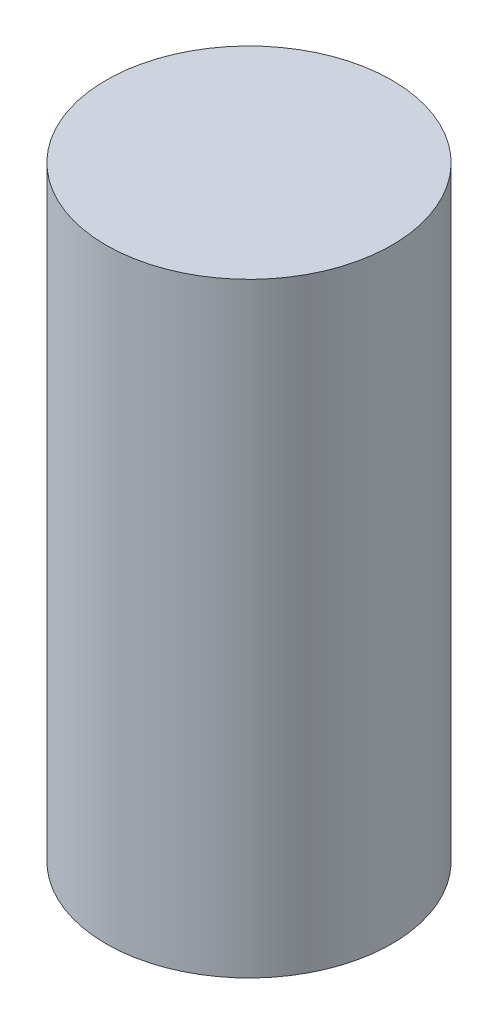
SolidWorks part; units mm, degrees
ref_plane "Front Plane" through (0, 0, 0) normal (0, 0, 1) x (1, 0, 0)
ref_plane "Top Plane" through (0, 0, 0) normal (0, 1, 0) x (1, 0, 0)
ref_plane "Right Plane" through (0, 0, 0) normal (1, 0, 0) x (0, 0, -1)
sketch "Sketch1" plane through (0, 0, 0) normal (0, 1, 0) x (1, 0, 0)
  circle A0 centre (0, 0) radius 60
  dimension "D1" = 120
extrude "Boss-Extrude1" add sketch "Sketch1" along normal blind 254
